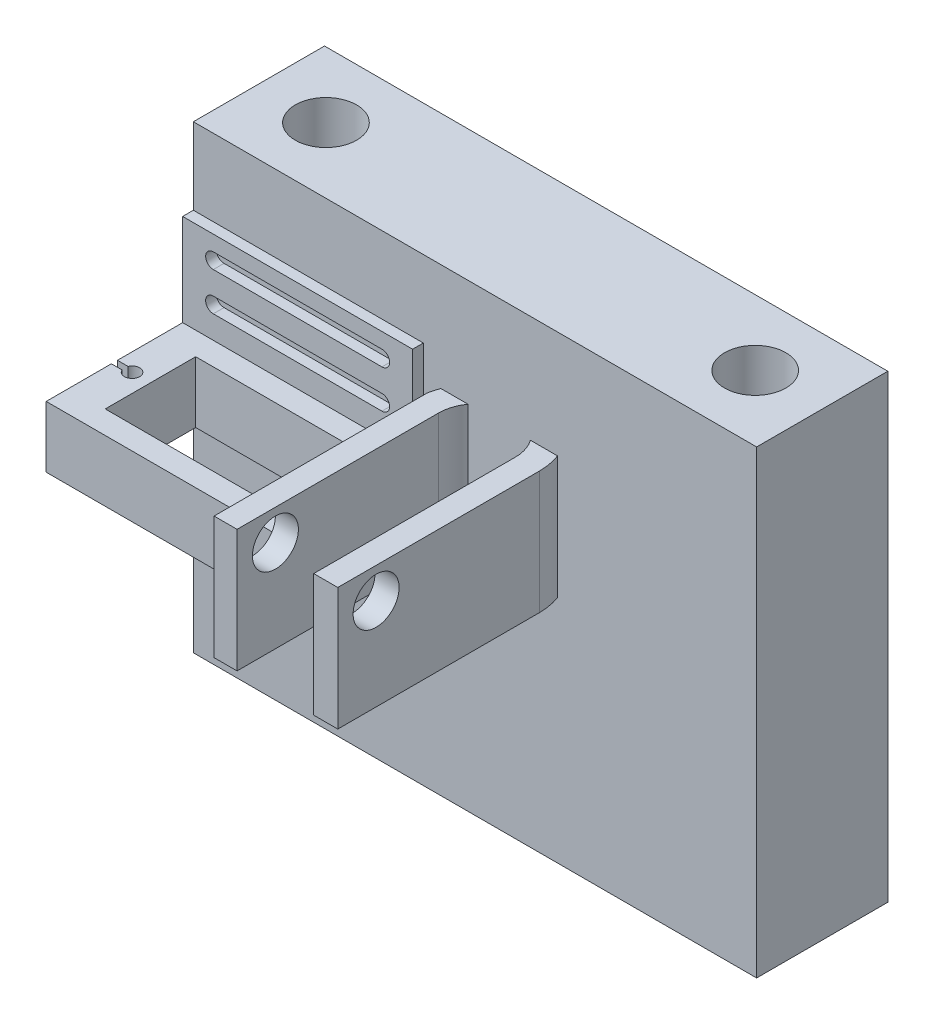
SolidWorks part; units mm, degrees
ref_plane "Front Plane" through (0, 0, 0) normal (0, 0, 1) x (1, 0, 0)
ref_plane "Top Plane" through (0, 0, 0) normal (0, 1, 0) x (1, 0, 0)
ref_plane "Right Plane" through (0, 0, 0) normal (1, 0, 0) x (0, 0, -1)
sketch "Sketch1" plane through (0, 0, 0) normal (0, 1, 0) x (1, 0, 0)
  line L1 (-15.95, -8.9) -> (15.95, -8.9)
  line L2 (-15.95, -8.9) -> (-15.95, 8.9)
  line L3 (-15.95, 8.9) -> (15.95, 8.9)
  line L4 (15.95, -8.9) -> (15.95, 8.9)
  line L5 (-15.95, -8.9) -> (15.95, 8.9) construction
  line L6 (-15.95, 8.9) -> (15.95, -8.9) construction
  line L7 (-11.25, -5.9) -> (11.25, -5.9)
  line L8 (-11.25, -5.9) -> (-11.25, 5.9)
  line L9 (-11.25, 5.9) -> (11.25, 5.9)
  line L10 (11.25, -5.9) -> (11.25, 5.9)
  line L11 (-11.25, -5.9) -> (11.25, 5.9) construction
  line L12 (-11.25, 5.9) -> (11.25, -5.9) construction
  point P0 (0, 0)
  point P6 (0, 0)
  dimension "D1" = 17.8
  dimension "D2" = 22.5
  dimension "D3" = 4.7
  dimension "D4" = 11.8
extrude "Boss-Extrude1" add sketch "Sketch1" along normal blind 8
sketch "Sketch3" plane through (0, 0, 0) normal (0, -1, 0) x (1, 0, 0)
  line L0 (28.95, -7.4) -> (28.95, 7.4)
  line L2 (32.0894, 7.4) -> (32.0894, -7.4)
  line L3 (18.95, -7.4) -> (18.95, 18.9)
  line L4 (18.95, 18.9) -> (15.95, 18.9)
  line L5 (15.95, 18.9) -> (15.95, -8.9)
  line L6 (28.95, 7.4) -> (28.95, 18.9)
  line L7 (15.95, -8.9) -> (23.95, -8.9)
  line L8 (28.95, 18.9) -> (32.0894, 18.9)
  line L9 (32.0894, 18.9) -> (32.0894, 7.4)
  arc A0 (18.95, -7.4) -> (28.95, -7.4) centre (23.95, -7.4) ccw
  arc A1 (15.95, -8.9) -> (32.0894, -7.4) centre (23.95, -7.4) ccw
  dimension "D1" = 27.8
  dimension "D3" = 5
extrude "Boss-Extrude2" add sketch "Sketch3" against normal blind 16
sketch "Sketch5" plane through (0, 0, -8.9) normal (0, 0, -1) x (-1, 0, 0)
  line L0 (0, 0) -> (0, 20)
  line L1 (0, 20) -> (15.95, 20)
  line L2 (15.95, 20) -> (15.95, 0)
  line L3 (15.95, 0) -> (-14.05, 0)
  line L4 (-15.95, 0) -> (15.95, 0) construction
  line L5 (-14.05, 0) -> (-14.05, 20)
  line L6 (-14.05, 20) -> (0, 20)
  line M7 (-15.95, 0) -> (15.95, 0)
  line M8 (15.95, 0) -> (15.95, 8)
  line M9 (15.95, 8) -> (-15.95, 8)
  dimension "D1" = 20
  dimension "D2" = 30
extrude "Boss-Extrude3" add sketch "Sketch5" along normal blind 3 contours L6 L5 L0 M9 | L2 L1 L0 M9 | L0 M7 M8 M9 | L5 L0 M7 M9
sketch "Sketch6" plane through (0, 0, -8.9) normal (0, 0, 1) x (1, 0, 0)
  line L0 (-11.95, 17) -> (10.05, 17) construction
  line L1 (-11.95, 18) -> (10.05, 18)
  line L2 (-11.95, 16) -> (10.05, 16)
  line L3 (-11.95, 12) -> (10.05, 12) construction
  line L4 (-11.95, 13) -> (10.05, 13)
  line L5 (-11.95, 11) -> (10.05, 11)
  line L6 (14.05, 20) -> (-15.95, 20) construction
  line L7 (-15.95, 20) -> (-15.95, 8) construction
  line L8 (14.05, 8) -> (14.05, 20) construction
  line L9 (-15.95, 8) -> (15.95, 8) construction
  arc A0 (-11.95, 18) -> (-11.95, 16) centre (-11.95, 17) ccw
  arc A1 (10.05, 16) -> (10.05, 18) centre (10.05, 17) ccw
  arc A2 (-11.95, 13) -> (-11.95, 11) centre (-11.95, 12) ccw
  arc A3 (10.05, 11) -> (10.05, 13) centre (10.05, 12) ccw
  point P2 (-0.95, 17)
  point P7 (-0.95, 12)
  dimension "D1" = 1
  dimension "D2" = 1
  dimension "D5" = 1
  dimension "D7" = 4
  dimension "D3" = 3
  dimension "D4" = 4
  dimension "D6" = 4
  dimension "D8" = 4
  dimension "D9" = 4
extrude "Cut-Extrude2" cut sketch "Sketch6" against normal blind 3 contours L2 A1 L1 A0 | L5 A3 L4 A2
sketch "Sketch7" plane through (0, 0, 0) normal (0, -1, 0) x (1, 0, 0)
  line L0 (-15.95, -11.9) -> (-15.95, 8.9) construction
  line L1 (-11.25, 5.9) -> (11.25, 5.9) construction
  line L2 (-13.65, 0) -> (-15.95, 0)
  line L3 (-15.95, -0.3939) -> (-15.95, 0.3939)
  line L4 (-15.95, 0.3939) -> (-14.5692, 0.3939)
  line L5 (-15.95, -0.3939) -> (-14.5692, -0.3939)
  arc A0 (-14.5692, -0.3939) -> (-14.5692, 0.3939) centre (-13.65, 0) ccw
  dimension "D2" = 2
  dimension "D1" = 2.3
  dimension "D3" = 5.9
extrude "Cut-Extrude3" cut sketch "Sketch7" against normal through all
mirror "Mirror1" about plane through (0, 0, 0) normal (1, 0, 0) of "Cut-Extrude3"
sketch "Sketch8" plane through (0, 0, 0) normal (0, -1, 0) x (1, 0, 0)
  line L0 (14.05, -11.9) -> (14.05, -8.9) construction
  line L1 (15.95, -8.9) -> (14.05, -8.9) construction
  line L2 (14.05, -11.9) -> (14.05, -8.9)
  line L3 (15.95, -8.9) -> (14.05, -8.9)
  line L4 (14.05, -11.9) -> (17.1677, -11.9)
  arc A0 (15.95, -8.9) -> (32.0894, -7.4) centre (23.95, -7.4) ccw construction
  arc A1 (15.95, -8.9) -> (17.1677, -11.9) centre (23.95, -7.4) ccw
extrude "Boss-Extrude4" add sketch "Sketch8" against normal up to vertex
sketch "Sketch9" plane through (15.95, 0, 0) normal (-1, 0, 0) x (0, 0, 1)
  line L0 (8.9, 8) -> (18.9, 8)
  line L1 (18.9, 16) -> (18.9, 0) construction
  line L2 (18.9, 8) -> (13.9, 8)
  line L3 (13.9, 8) -> (13.9, 16)
  line L4 (18.9, 16) -> (-8.9, 16) construction
  circle A0 centre (13.9, 12) radius 3
  dimension "D1" = 6
extrude "Cut-Extrude4" cut sketch "Sketch9" against normal through all contours L3 A0 | L3 A0
sketch "Çizim1" plane through (0, 0, 0) normal (0, -1, 0) x (1, 0, 0)
  line L0 (57.5338, -27.4091) -> (57.5338, -10.2983)
  line L1 (57.5338, -10.2983) -> (-15.95, -10.2983)
  line L2 (-15.95, -10.2983) -> (-15.95, -27.4091)
  line L3 (-15.95, -27.4091) -> (57.5338, -27.4091)
  circle A0 centre (48.7919, -18.8537) radius 4
  circle A1 centre (-7.2081, -18.8537) radius 4
extrude "Yükseklik-Ekstrüzyon1" add sketch "Çizim1" along normal mid plane 60
